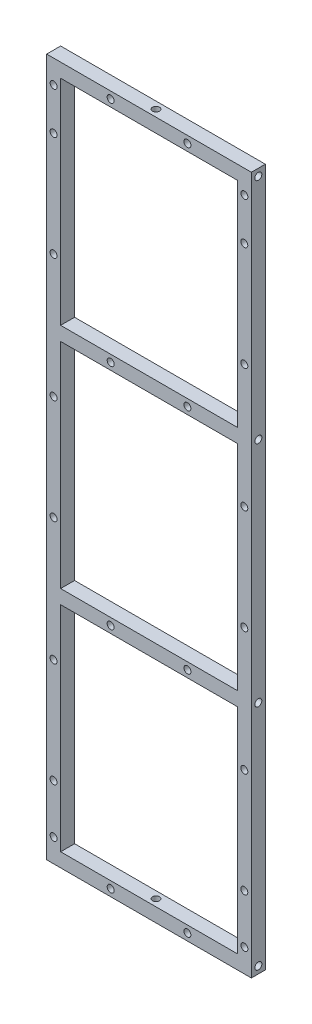
SolidWorks part; units mm, degrees
ref_plane "Front Plane" through (0, 0, 0) normal (0, 0, 1) x (1, 0, 0)
ref_plane "Top Plane" through (0, 0, 0) normal (0, 1, 0) x (1, 0, 0)
ref_plane "Right Plane" through (0, 0, 0) normal (1, 0, 0) x (0, 0, -1)
sketch "Sketch1" plane through (0, 0, 0) normal (0, 0, 1) x (1, 0, 0)
  line L0 (38, 144) -> (38, 52)
  line L9 (-44, -150) -> (44, -150)
  line L10 (-44, -150) -> (-44, 150)
  line L11 (-44, 150) -> (44, 150)
  line L12 (44, -150) -> (44, 150)
  line L15 (-38, -144) -> (38, -144)
  line L16 (-38, -144) -> (-38, -52)
  line L17 (-38, 144) -> (38, 144)
  line L21 (-38, 52) -> (38, 52)
  line L23 (-38, 46) -> (38, 46)
  line L25 (-38, -46) -> (38, -46)
  line L27 (-38, -52) -> (38, -52)
  line L33 (38, 46) -> (38, -46)
  line L34 (-38, 52) -> (-38, 144)
  line L35 (-38, -46) -> (-38, 46)
  line L36 (38, -52) -> (38, -144)
  point P0 (0, 0)
  point P4 (0, -46)
  point P6 (0, 0)
  point P20 (0, 0)
  point P21 (0, -150)
  dimension "D1" = 88
  dimension "D2" = 300
  dimension "D3" = 76
  dimension "D4" = 288
  dimension "D5" = 6
  dimension "D6" = 92
  dimension "D7" = 6
  dimension "D8" = 92
  dimension "D9" = 6
  dimension "D10" = 6
  dimension "D11" = 92
extrude "Boss-Extrude1" add sketch "Sketch1" along normal blind 6
sketch "Sketch2" plane through (44, 0, 0) normal (1, 0, 0) x (0, 0, -1)
  line L0 (-6, 150) -> (0, 150) construction
  circle A0 centre (-3, 147) radius 1.5
  circle A1 centre (-3, 49) radius 1.5
  circle A2 centre (-3, -49) radius 1.5
  circle A3 centre (-3, -147) radius 1.5
  dimension "D1" = 3
  dimension "D2" = 4
extrude "Cut-Extrude1" cut sketch "Sketch2" against normal blind 10
mirror "Mirror1" about plane through (0, 0, 0) normal (1, 0, 0) of "Cut-Extrude1"
sketch "Sketch3" plane through (0, 0, 6) normal (0, 0, 1) x (1, 0, 0)
  line L0 (-44, 150) -> (44, 150) construction
  line L1 (-44, -150) -> (-44, 150) construction
  circle A0 centre (-41, 140) radius 1.5
  circle A1 centre (41, 140) radius 1.5
  circle A2 centre (41, -140) radius 1.5
  circle A3 centre (-41, -140) radius 1.5
  dimension "D1" = 10
  dimension "D2" = 3
  dimension "D3" = 2
  dimension "D4" = 2
extrude "Cut-Extrude2" cut sketch "Sketch3" against normal blind 10
sketch "Sketch4" plane through (0, 0, 6) normal (0, 0, 1) x (1, 0, 0)
  line L0 (-44, -150) -> (-44, 150) construction
  line L1 (44, -150) -> (44, 150) construction
  line L2 (-44, 150) -> (44, 150) construction
  circle A0 centre (-16.5, 147) radius 1.5
  circle A1 centre (16.5, 147) radius 1.5
  circle A2 centre (16.5, 49) radius 1.5
  circle A3 centre (-16.5, 49) radius 1.5
  circle A4 centre (16.5, -49) radius 1.5
  circle A5 centre (-16.5, -49) radius 1.5
  circle A6 centre (16.5, -147) radius 1.5
  circle A7 centre (-16.5, -147) radius 1.5
  circle A8 centre (-41.0409, 122) radius 1.5
  circle A9 centre (-41.0409, 77) radius 1.5
  circle A10 centre (40.9591, 122) radius 1.5
  circle A11 centre (40.9591, 77) radius 1.5
  circle A12 centre (40.9591, 24) radius 1.5
  circle A13 centre (40.9591, -21) radius 1.5
  circle A14 centre (40.9591, -74) radius 1.5
  circle A15 centre (40.9591, -119) radius 1.5
  circle A16 centre (-41.0409, 24) radius 1.5
  circle A17 centre (-41.0409, -21) radius 1.5
  circle A18 centre (-41.0409, -74) radius 1.5
  circle A19 centre (-41.0409, -119) radius 1.5
  dimension "D1" = 27.5
  dimension "D4" = 45
  dimension "D7" = 2
  dimension "D2" = 27.5
  dimension "D3" = 4
  dimension "D5" = 28
  dimension "D6" = 28
  dimension "D8" = 3
extrude "Cut-Extrude3" cut sketch "Sketch4" against normal blind 10
sketch "Sketch5" plane through (0, 150, 0) normal (0, 1, 0) x (1, 0, 0)
  line L0 (44, -6) -> (-44, -6) construction
  circle A0 centre (0, -3) radius 1.5
  point P5 (0, -6)
  dimension "D1" = 3
extrude "Cut-Extrude4" cut sketch "Sketch5" against normal blind 10
mirror "Mirror2" about plane through (0, 0, 0) normal (0, 1, 0) of "Cut-Extrude4"
